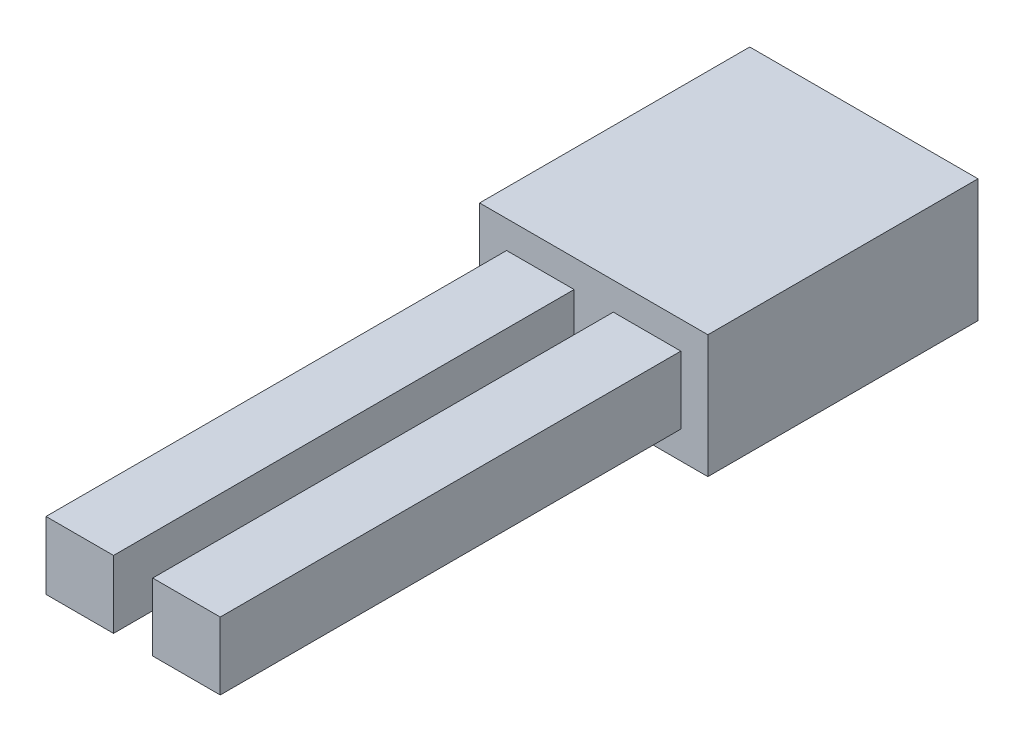
SolidWorks part; units mm, degrees
other "Markup1"
sketch "Sketch3" plane through (0, 1.82, 6.82) normal (-0.1168, 0.9143, 0.3878) x (0.9373, 0.2306, -0.2614)
ref_plane "Front Plane" through (0, 0, 0) normal (0, 0, 1) x (1, 0, 0)
ref_plane "Top Plane" through (0, 0, 0) normal (0, 1, 0) x (1, 0, 0)
ref_plane "Right Plane" through (0, 0, 0) normal (1, 0, 0) x (0, 0, -1)
sketch "Sketch1" plane through (0, 0, 0) normal (0, 1, 0) x (1, 0, 0)
  line L1 (0, 0) -> (3.38, 0)
  line L2 (0, 0) -> (0, 4)
  line L3 (0, 4) -> (3.38, 4)
  line L4 (3.38, 0) -> (3.38, 4)
  dimension "D1" = 3.38
  dimension "D2" = 4
extrude "Boss-Extrude1" add sketch "Sketch1" along normal blind 1.82
sketch "Sketch2" plane through (0, 0, 0) normal (0, 0, 1) x (1, 0, 0)
  line L0 (0, 1.82) -> (0, 0) construction
  line L1 (0.4, 1.41) -> (1.4, 1.41)
  line L2 (0.4, 1.41) -> (0.4, 0.41)
  line L3 (0.4, 0.41) -> (1.4, 0.41)
  line L4 (1.4, 1.41) -> (1.4, 0.41)
  line L5 (1.98, 1.41) -> (2.98, 1.41)
  line L6 (1.98, 1.41) -> (1.98, 0.41)
  line L7 (1.98, 0.41) -> (2.98, 0.41)
  line L8 (2.98, 1.41) -> (2.98, 0.41)
  line L9 (0, 1.82) -> (3.38, 1.82) construction
  line L10 (0, 0) -> (3.38, 0) construction
  line L11 (3.38, 1.82) -> (3.38, 0) construction
  dimension "D1" = 1
  dimension "D2" = 1
  dimension "D3" = 0.4
  dimension "D4" = 0.41
  dimension "D5" = 0.41
  dimension "D6" = 1
  dimension "D7" = 1
  dimension "D8" = 0.41
  dimension "D9" = 0.41
  dimension "D10" = 0.4
extrude "Boss-Extrude2" add sketch "Sketch2" along normal blind 6.82
